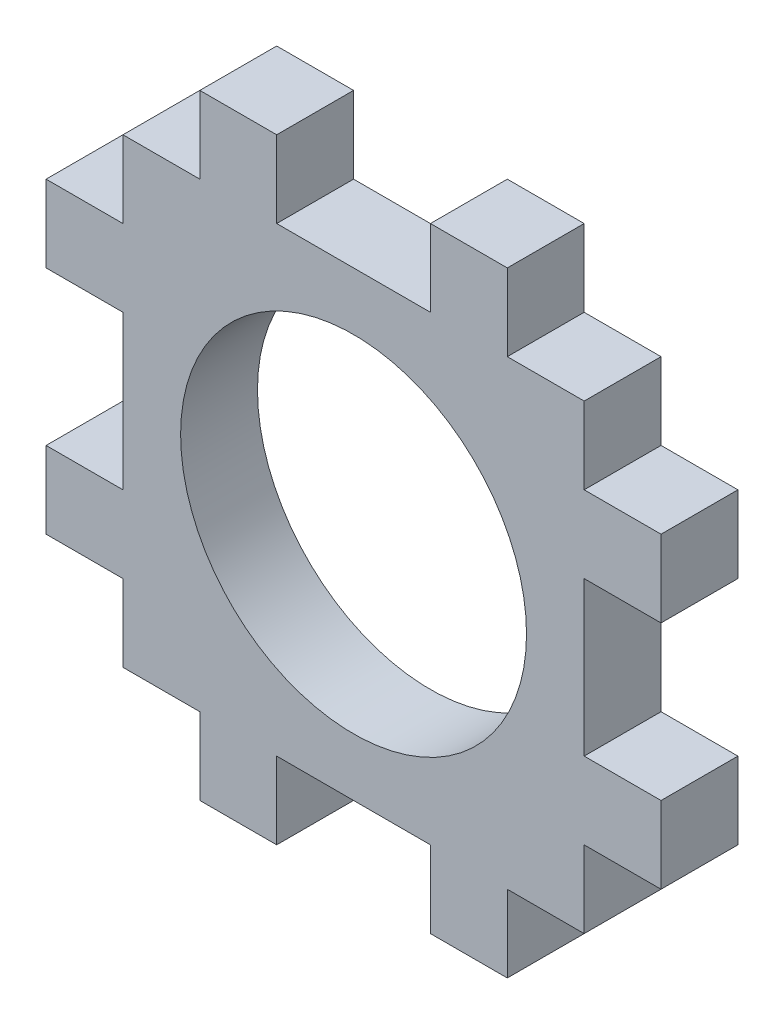
SolidWorks part; units mm, degrees
ref_plane "Front Plane" through (0, 0, 0) normal (0, 0, 1) x (1, 0, 0)
ref_plane "Top Plane" through (0, 0, 0) normal (0, 1, 0) x (1, 0, 0)
ref_plane "Right Plane" through (0, 0, 0) normal (1, 0, 0) x (0, 0, -1)
sketch "Sketch1" plane through (0, 0, 0) normal (0, 0, 1) x (1, 0, 0)
  line L0 (-15, 15) -> (15, 15) construction
  line L1 (15, 15) -> (15, -15) construction
  line L2 (15, -15) -> (-15, -15) construction
  line L3 (-15, -15) -> (-15, 15) construction
  line L4 (5, 15) -> (-5, 15)
  line L5 (0, 0) -> (0, -29.0372) construction
  line L6 (5, 20) -> (10, 20)
  line L7 (10, 20) -> (10, 15)
  line L8 (5, 20) -> (5, 15)
  line L9 (-15, 15) -> (-10, 15)
  line L10 (-5, 15) -> (-5, 20)
  line L11 (-5, 20) -> (-10, 20)
  line L12 (-10, 20) -> (-10, 15)
  line L13 (10, 15) -> (15, 15)
  line L14 (15, 15) -> (15, 10)
  line L15 (20, 10) -> (15, 10)
  line L16 (20, 5) -> (20, 10)
  line L17 (15, 5) -> (20, 5)
  line L18 (15, -5) -> (15, 5)
  line L19 (20, -5) -> (15, -5)
  line L20 (20, -5) -> (20, -10)
  line L21 (20, -10) -> (15, -10)
  line L22 (15, -10) -> (15, -15)
  line L23 (15, -15) -> (10, -15)
  line L24 (10, -20) -> (10, -15)
  line L25 (5, -20) -> (10, -20)
  line L26 (5, -15) -> (5, -20)
  line L27 (-5, -15) -> (5, -15)
  line L28 (-5, -20) -> (-5, -15)
  line L29 (-5, -20) -> (-10, -20)
  line L30 (-10, -20) -> (-10, -15)
  line L31 (-10, -15) -> (-15, -15)
  line L32 (-15, -15) -> (-15, -10)
  line L33 (-20, -10) -> (-15, -10)
  line L34 (-20, -5) -> (-20, -10)
  line L35 (-15, -5) -> (-20, -5)
  line L36 (-15, 5) -> (-15, -5)
  line L37 (-20, 5) -> (-15, 5)
  line L38 (-20, 5) -> (-20, 10)
  line L39 (-20, 10) -> (-15, 10)
  line L40 (-15, 10) -> (-15, 15)
  circle A0 centre (0, 0) radius 11.25
  point P6 (0, -15)
  point P49 (0, 0)
  dimension "D7" = 22.5
  dimension "D1" = 10
  dimension "D2" = 5
  dimension "D3" = 5
  dimension "D4" = 15
  dimension "D5" = 15
  dimension "D6" = 4
extrude "Boss-Extrude1" add sketch "Sketch1" along normal blind 5
